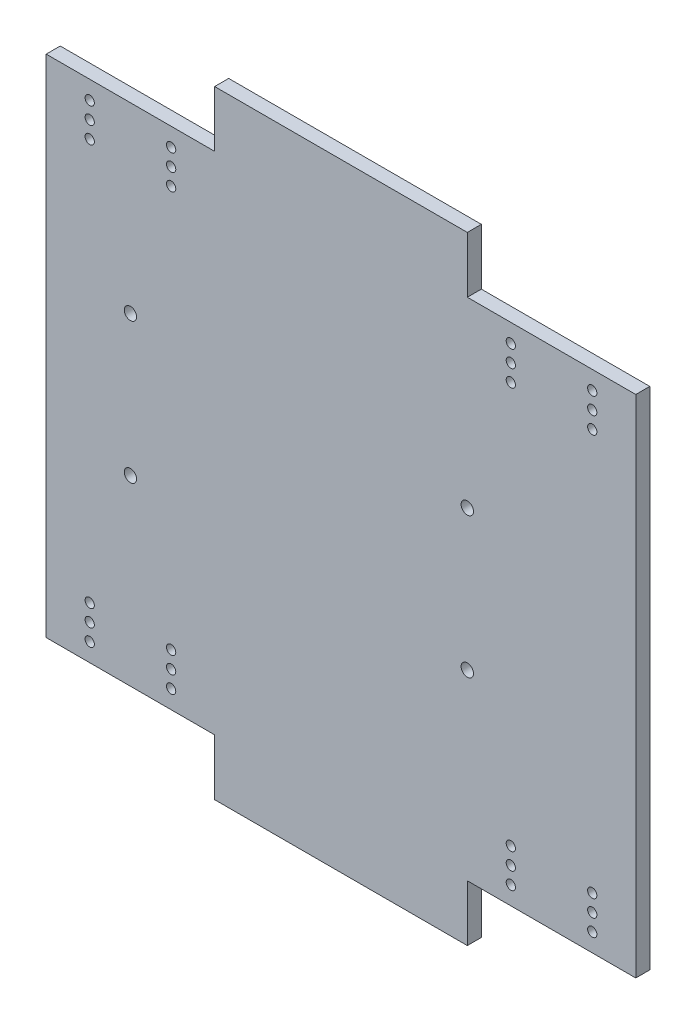
SolidWorks part; units mm, degrees
ref_plane "Front Plane" through (0, 0, 0) normal (0, 0, 1) x (1, 0, 0)
ref_plane "Top Plane" through (0, 0, 0) normal (0, 1, 0) x (1, 0, 0)
ref_plane "Right Plane" through (0, 0, 0) normal (1, 0, 0) x (0, 0, -1)
sketch "Sketch2" plane through (0, 0, 0) normal (0, 0, 1) x (1, 0, 0)
  line L1 (-105, -90) -> (105, -90)
  line L2 (-105, -90) -> (-105, 90)
  line L3 (-105, 90) -> (105, 90)
  line L4 (105, -90) -> (105, 90)
  line L5 (-105, -90) -> (105, 90) construction
  line L6 (-105, 90) -> (105, -90) construction
  point P0 (0, 0)
  dimension "D1" = 210
  dimension "D2" = 180
extrude "Boss-Extrude1" add sketch "Sketch2" along normal blind 5
sketch "Sketch3" plane through (0, -90, 0) normal (0, -1, 0) x (-1, 0, 0)
  line L0 (105, -5) -> (-105, -5) construction
  line L1 (45, -5) -> (-45, -5)
  line L2 (45, -5) -> (45, 0)
  line L3 (45, 0) -> (-45, 0)
  line L4 (-45, -5) -> (-45, 0)
  line L5 (105, 0) -> (-105, 0) construction
  line L6 (105, -5) -> (105, 0) construction
  dimension "D1" = 90
  dimension "D2" = 60
extrude "Boss-Extrude2" add sketch "Sketch3" along normal blind 20
sketch "Sketch4" plane through (0, 90, 0) normal (0, 1, 0) x (1, 0, 0)
  line L0 (105, 0) -> (-105, 0) construction
  line L1 (-45, 0) -> (45, 0)
  line L2 (-45, 0) -> (-45, -5)
  line L3 (-45, -5) -> (45, -5)
  line L4 (45, 0) -> (45, -5)
  line L5 (105, -5) -> (-105, -5) construction
  line L6 (-105, -5) -> (-105, 0) construction
  dimension "D1" = 90
  dimension "D2" = 60
extrude "Boss-Extrude3" add sketch "Sketch4" along normal blind 20
sketch "Sketch5" plane through (0, 0, 5) normal (0, 0, 1) x (1, 0, 0)
  line L0 (105, 90) -> (45, 90) construction
  line L1 (105, -90) -> (105, 90) construction
  line L2 (0, -1000) -> (0, 49000) construction
  line L3 (-1000, 0) -> (49000, 0) construction
  line L4 (-45, 110) -> (45, 110) construction
  line L5 (45, -110) -> (-45, -110) construction
  line L6 (-105, 90) -> (-105, -90) construction
  circle A0 centre (89.5, 83.5) radius 1.65
  circle A1 centre (89.5, 77.5) radius 1.65
  circle A2 centre (89.5, 71.5) radius 1.65
  circle A3 centre (60.5, 83.5) radius 1.65
  circle A4 centre (60.5, 77.5) radius 1.65
  circle A5 centre (60.5, 71.5) radius 1.65
  circle A6 centre (-60.5, 71.5) radius 1.65
  circle A7 centre (-60.5, 77.5) radius 1.65
  circle A8 centre (-60.5, 83.5) radius 1.65
  circle A9 centre (-89.5, 71.5) radius 1.65
  circle A10 centre (-89.5, 77.5) radius 1.65
  circle A11 centre (-89.5, 83.5) radius 1.65
  circle A12 centre (-89.5, -83.5) radius 1.65
  circle A13 centre (-89.5, -77.5) radius 1.65
  circle A14 centre (-89.5, -71.5) radius 1.65
  circle A15 centre (-60.5, -83.5) radius 1.65
  circle A16 centre (-60.5, -77.5) radius 1.65
  circle A17 centre (-60.5, -71.5) radius 1.65
  circle A18 centre (60.5, -71.5) radius 1.65
  circle A19 centre (60.5, -77.5) radius 1.65
  circle A20 centre (60.5, -83.5) radius 1.65
  circle A21 centre (89.5, -71.5) radius 1.65
  circle A22 centre (89.5, -77.5) radius 1.65
  circle A23 centre (89.5, -83.5) radius 1.65
  circle A24 centre (45, 25) radius 2.2
  circle A25 centre (45, -25) radius 2.2
  circle A26 centre (-75, 25) radius 2.2
  circle A27 centre (-75, -25) radius 2.2
  dimension "D7" = 3.3
  dimension "D8" = 3.3
  dimension "D9" = 3.3
  dimension "D12" = 60
  dimension "D14" = 4.4
  dimension "D17" = 4.4
  dimension "D20" = 4.4
  dimension "D21" = 4.4
  dimension "D1" = 6.5
  dimension "D2" = 15.5
  dimension "D3" = 15.5
  dimension "D4" = 6
  dimension "D5" = 15.5
  dimension "D6" = 6
  dimension "D11" = 29
  dimension "D13" = 85
  dimension "D15" = 60
  dimension "D16" = 85
  dimension "D18" = 120
  dimension "D19" = 120
  dimension "D22" = 30
  dimension "D23" = 30
  dimension "D10" = 2
extrude "Cut-Extrude1" cut sketch "Sketch5" against normal through all
